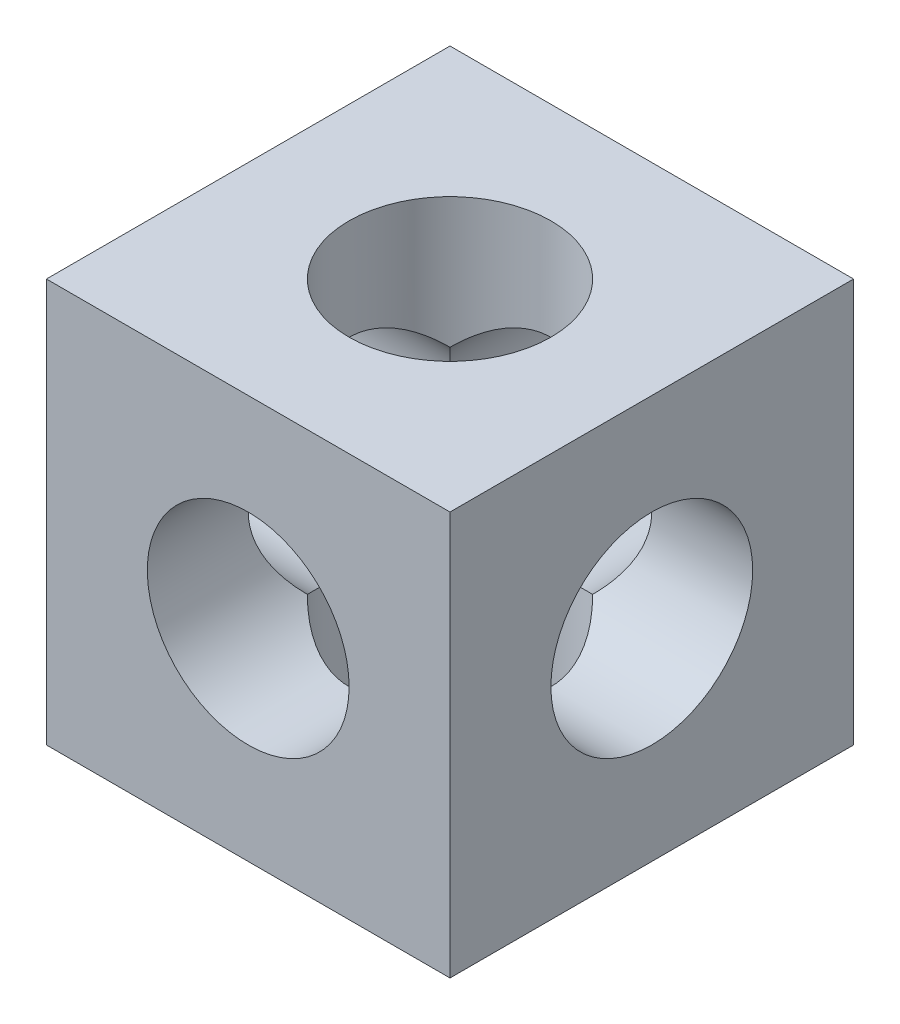
SolidWorks part; units mm, degrees
material "1060 合金"
ref_plane "前视基准面" through (0, 0, 0) normal (0, 0, 1) x (1, 0, 0)
ref_plane "上视基准面" through (0, 0, 0) normal (0, 1, 0) x (1, 0, 0)
ref_plane "右视基准面" through (0, 0, 0) normal (1, 0, 0) x (0, 0, -1)
other "Configuration Table"
sketch "草图1" plane through (0, 0, 0) normal (0, 0, 1) x (1, 0, 0)
  line L1 (-3, 3) -> (3, 3)
  line L2 (-3, 3) -> (-3, -3)
  line L3 (-3, -3) -> (3, -3)
  line L4 (3, 3) -> (3, -3)
  line L5 (-3, 3) -> (3, -3) construction
  line L6 (-3, -3) -> (3, 3) construction
  point P0 (0, 0)
  dimension "D1" = 6
  dimension "D2" = 6
extrude "凸台-拉伸1" add sketch "草图1" along normal mid plane 6
sketch "草图2" plane through (-3, 0, 0) normal (-1, 0, 0) x (0, 0, 1)
  circle A0 centre (0, 0) radius 1.5
extrude "切除-拉伸1" cut sketch "草图2" against normal blind 8
sketch "草图3" plane through (0, 3, 0) normal (0, 1, 0) x (1, 0, 0)
  circle A0 centre (0, 0) radius 1.5
extrude "切除-拉伸2" cut sketch "草图3" against normal blind 8
sketch "草图4" plane through (0, 0, -3) normal (0, 0, -1) x (-1, 0, 0)
  circle A0 centre (0, 0) radius 1.5
extrude "切除-拉伸3" cut sketch "草图4" against normal blind 8
